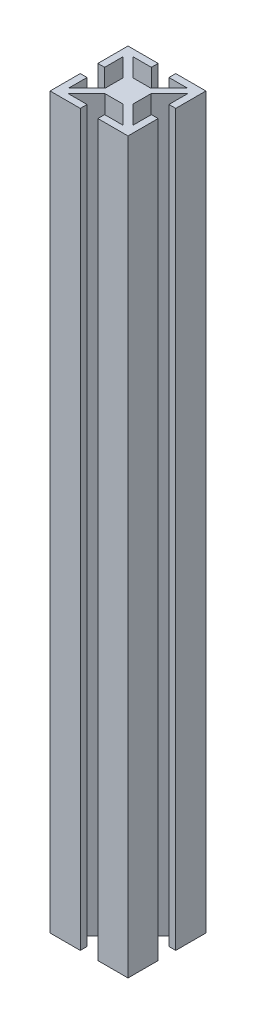
SolidWorks part; units mm, degrees
ref_plane "Front Plane" through (0, 0, 0) normal (0, 0, 1) x (1, 0, 0)
ref_plane "Top Plane" through (0, 0, 0) normal (0, 1, 0) x (1, 0, 0)
ref_plane "Right Plane" through (0, 0, 0) normal (1, 0, 0) x (0, 0, -1)
sketch "Sketch1" plane through (11.365, 0, 9.8462) normal (0, 1, 0) x (1, 0, 0)
  line L0 (-11.365, 9.8462) -> (-11.365, 32.3924) construction
  line L1 (-11.365, 9.8462) -> (-35.43, 9.8462) construction
  line L2 (-11.365, 9.8462) -> (-7.5972, 6.0784) construction
  line L3 (-24.065, 22.5462) -> (-14.2298, 22.5462)
  line L4 (-14.2298, 22.5462) -> (-14.2298, 20.3364)
  line L5 (-14.2298, 20.3364) -> (-20.2926, 20.3364)
  line L6 (-20.2926, 20.3364) -> (-14.3109, 14.3547)
  line L7 (-14.3109, 14.3547) -> (-8.4191, 14.3547)
  line L8 (-15.8735, 12.7921) -> (-15.8735, 6.9003)
  line L9 (-21.8552, 18.7738) -> (-15.8735, 12.7921)
  line L10 (-21.8552, 12.711) -> (-21.8552, 18.7738)
  line L11 (-24.065, 12.711) -> (-21.8552, 12.711)
  line L12 (-24.065, 22.5462) -> (-24.065, 12.711)
  line L13 (-14.3109, 5.3377) -> (-8.4191, 5.3377)
  line L14 (-20.2926, -0.644) -> (-14.3109, 5.3377)
  line L15 (-21.8552, 0.9186) -> (-15.8735, 6.9003)
  line L16 (-21.8552, 6.9814) -> (-21.8552, 0.9186)
  line L17 (-24.065, 6.9814) -> (-21.8552, 6.9814)
  line L18 (-24.065, -2.8538) -> (-24.065, 6.9814)
  line L19 (-14.2298, -0.644) -> (-20.2926, -0.644)
  line L20 (-14.2298, -2.8538) -> (-14.2298, -0.644)
  line L21 (-24.065, -2.8538) -> (-14.2298, -2.8538)
  line L22 (1.335, -2.8538) -> (-8.5002, -2.8538)
  line L23 (-8.5002, -2.8538) -> (-8.5002, -0.644)
  line L24 (-8.5002, -0.644) -> (-2.4374, -0.644)
  line L25 (1.335, -2.8538) -> (1.335, 6.9814)
  line L26 (1.335, 6.9814) -> (-0.8748, 6.9814)
  line L27 (-0.8748, 6.9814) -> (-0.8748, 0.9186)
  line L28 (-0.8748, 0.9186) -> (-6.8565, 6.9003)
  line L29 (-2.4374, -0.644) -> (-8.4191, 5.3377)
  line L30 (1.335, 22.5462) -> (1.335, 12.711)
  line L31 (1.335, 12.711) -> (-0.8748, 12.711)
  line L32 (-0.8748, 12.711) -> (-0.8748, 18.7738)
  line L33 (-0.8748, 18.7738) -> (-6.8565, 12.7921)
  line L34 (-6.8565, 12.7921) -> (-6.8565, 6.9003)
  line L35 (-2.4374, 20.3364) -> (-8.4191, 14.3547)
  line L36 (-8.5002, 20.3364) -> (-2.4374, 20.3364)
  line L37 (-8.5002, 22.5462) -> (-8.5002, 20.3364)
  line L38 (1.335, 22.5462) -> (-8.5002, 22.5462)
  point P20 (-15.8735, 9.8462)
  point P26 (-6.8565, 9.8462)
  point P36 (-11.365, 5.3377)
  point P42 (-11.365, 14.3547)
  dimension "D1" = 9.8352
  dimension "D2" = 12.7
  dimension "D3" = 4.5085
  dimension "D4" = 2.2098
  dimension "D5" = 1.1049
extrude "Boss-Extrude1" add sketch "Sketch1" along normal up to surface (237.8551 mm away)
other "1010<1>"
